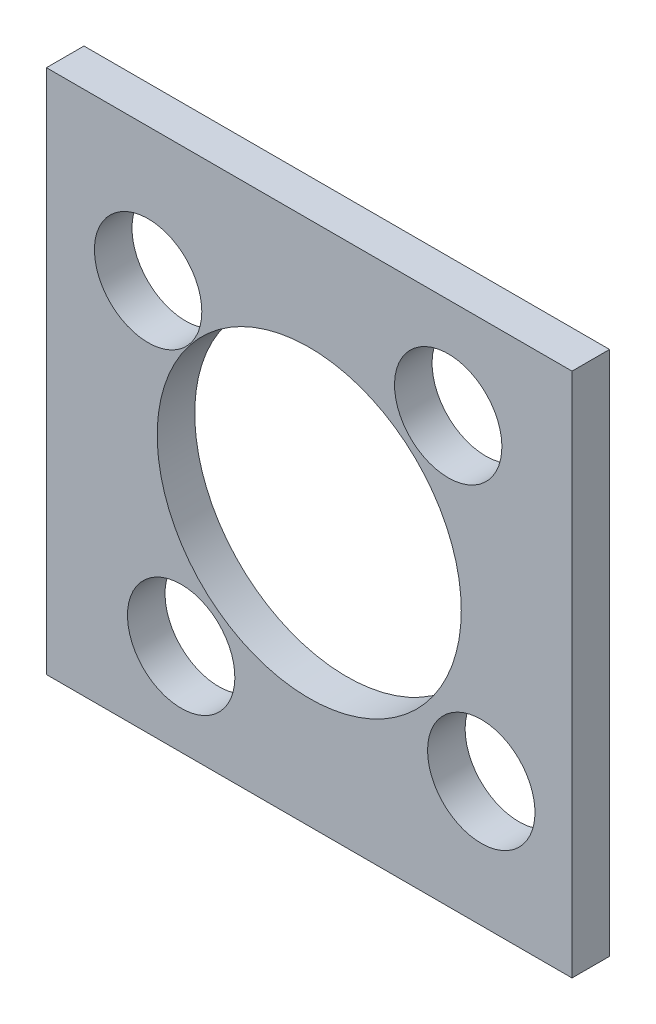
SolidWorks part; units mm, degrees
ref_plane "Front Plane" through (0, 0, 0) normal (0, 0, 1) x (1, 0, 0)
ref_plane "Top Plane" through (0, 0, 0) normal (0, 1, 0) x (1, 0, 0)
ref_plane "Right Plane" through (0, 0, 0) normal (1, 0, 0) x (0, 0, -1)
sketch "Sketch2" plane through (0, 0, 0) normal (0, 0, 1) x (1, 0, 0)
  line L1 (-70, 70) -> (70, 70)
  line L2 (-70, 70) -> (-70, -70)
  line L3 (-70, -70) -> (70, -70)
  line L4 (70, 70) -> (70, -70)
  line L5 (-70, 70) -> (70, -70) construction
  line L6 (-70, -70) -> (70, 70) construction
  point P0 (0, 0)
  dimension "D1" = 140
  dimension "D2" = 140
extrude "Boss-Extrude1" add sketch "Sketch2" along normal blind 10
sketch "Sketch3" plane through (0, 0, 10) normal (0, 0, 1) x (1, 0, 0)
  circle A0 centre (-42.9154, 34.3987) radius 14.3
  dimension "D1" = 55
extrude "Cut-Extrude1" cut sketch "Sketch3" against normal through all
pattern_circular "CirPattern1" count 4 over 360 about axis through (1.4543, -1.1657, 0) along (0, 0, 1) of "Cut-Extrude1"
sketch "Sketch4" plane through (0, 0, 10) normal (0, 0, 1) x (1, 0, 0)
  circle A0 centre (0, 0) radius 40.5
extrude "Cut-Extrude2" cut sketch "Sketch4" against normal through all
